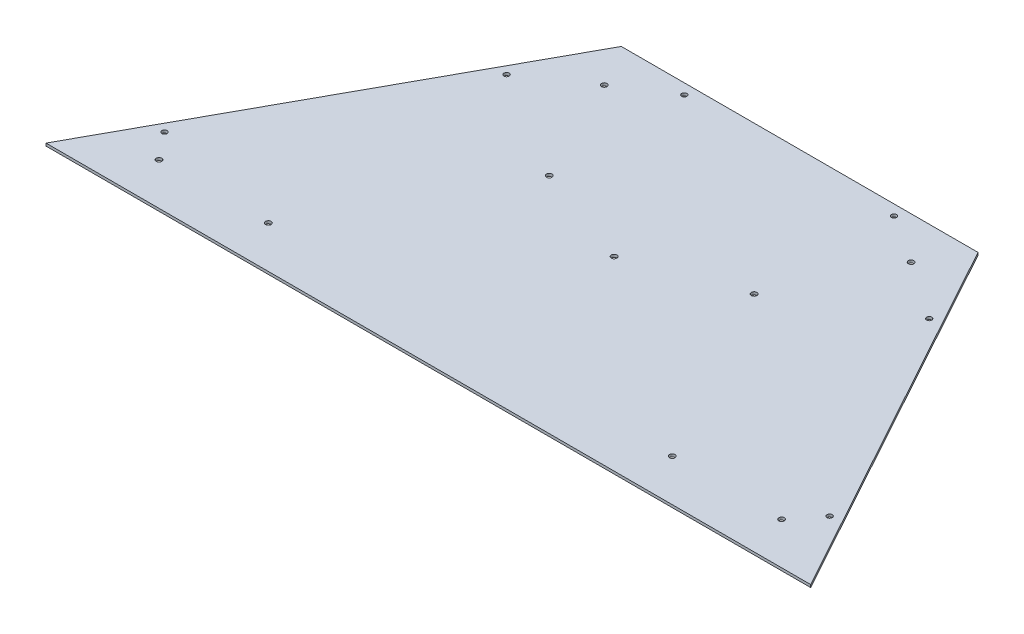
SolidWorks part; units mm, degrees
material "PC High Viscosity"
ref_plane "Front Plane" through (0, 0, 0) normal (0, 0, 1) x (1, 0, 0)
ref_plane "Top Plane" through (0, 0, 0) normal (0, 1, 0) x (1, 0, 0)
ref_plane "Right Plane" through (0, 0, 0) normal (1, 0, 0) x (0, 0, -1)
sketch "Sketch1" plane through (0, 0, 0) normal (0, 1, 0) x (1, 0, 0)
  line L0 (-462.534, 0) -> (-215.773, 449.265)
  line L1 (-215.773, 449.265) -> (215.773, 449.265)
  line L2 (215.773, 449.265) -> (462.534, 0)
  line L3 (462.534, 0) -> (-462.534, 0)
  point P2 (0, 0)
  dimension "D1" = 925.068
  dimension "D2" = 512.572
  dimension "D3" = 431.546
extrude "Boss-Extrude1" add sketch "Sketch1" along normal blind 3.175
hole_wizard "1/4 (0.25) Diameter Hole1" positions "Sketch2" profile "Sketch3" hole size "1/4" standard "ANSI Inch" end condition through all
sketch "Sketch2" plane through (0, 3.175, 0) normal (0, 1, 0) x (1, 0, 0)
  line L0 (0, 0) -> (0, 449.265) construction
  line L1 (215.773, 449.265) -> (-215.773, 449.265) construction
  line L3 (-402.3683, 83.1602) -> (-413.4997, 89.2742) construction
  line L4 (-215.773, 449.265) -> (-462.534, 0) construction
  line L6 (-255.6323, 350.3148) -> (-266.7638, 356.4288) construction
  line L8 (-126.873, 436.565) -> (-126.873, 449.265) construction
  point P0 (-402.3683, 83.1602)
  point P2 (-255.6323, 350.3148)
  point P4 (-126.873, 436.565)
  point P33 (402.3683, 83.1602)
  point P34 (255.6323, 350.3148)
  point P35 (126.873, 436.565)
  dimension "D1" = 101.854
  dimension "D2" = 406.654
  dimension "D3" = 12.7
  dimension "D4" = 88.9
sketch "Sketch3" plane through (-402.3683, 3.175, -83.1602) normal (1, 0, 0) x (0, 0, 1)
  line L0 (0, 0) -> (0, 3.175)
  line L1 (0, 3.175) -> (3.175, 3.175)
  line L2 (3.175, 3.175) -> (3.175, 0)
  line L5 (3.175, 0) -> (0, 0)
  line L11 (0, -6.35) -> (0, 107.95) construction
  dimension "Thru Hole Dia." = 6.35
  dimension "Thru Hole Depth" = 3.175
hole_wizard "1/4 Clearance Hole1" positions "Sketch4" profile "Sketch5" hole size "1/4" standard "ANSI Inch" end condition through all
sketch "Sketch4" plane through (0, 3.175, 0) normal (0, 1, 0) x (1, 0, 0)
  line L0 (0, 0) -> (0, 449.265) construction
  line L1 (215.773, 449.265) -> (-215.773, 449.265) construction
  line L3 (-462.534, 0) -> (462.534, 0) construction
  point P0 (-376.682, 50.8)
  point P2 (-244.348, 50.8)
  point P4 (-123.952, 270.256)
  point P6 (-185.674, 398.526)
  point P19 (0, 224.79)
  point P28 (376.682, 50.8)
  point P29 (244.348, 50.8)
  point P30 (185.674, 398.526)
  point P31 (123.952, 270.256)
  dimension "D1" = 50.8
  dimension "D2" = 244.348
  dimension "D3" = 376.682
  dimension "D4" = 123.952
  dimension "D5" = 270.256
  dimension "D6" = 185.674
  dimension "D7" = 398.526
  dimension "D8" = 224.79
sketch "Sketch5" plane through (-376.682, 3.175, -50.8) normal (1, 0, 0) x (0, 0, 1)
  line L0 (0, 0) -> (0, 3.175)
  line L1 (0, 3.175) -> (3.3782, 3.175)
  line L2 (3.3782, 3.175) -> (3.3782, 0)
  line L5 (3.3782, 0) -> (0, 0)
  line L11 (0, -6.35) -> (0, 107.95) construction
  dimension "Thru Hole Dia." = 6.7564
  dimension "Thru Hole Depth" = 3.175
